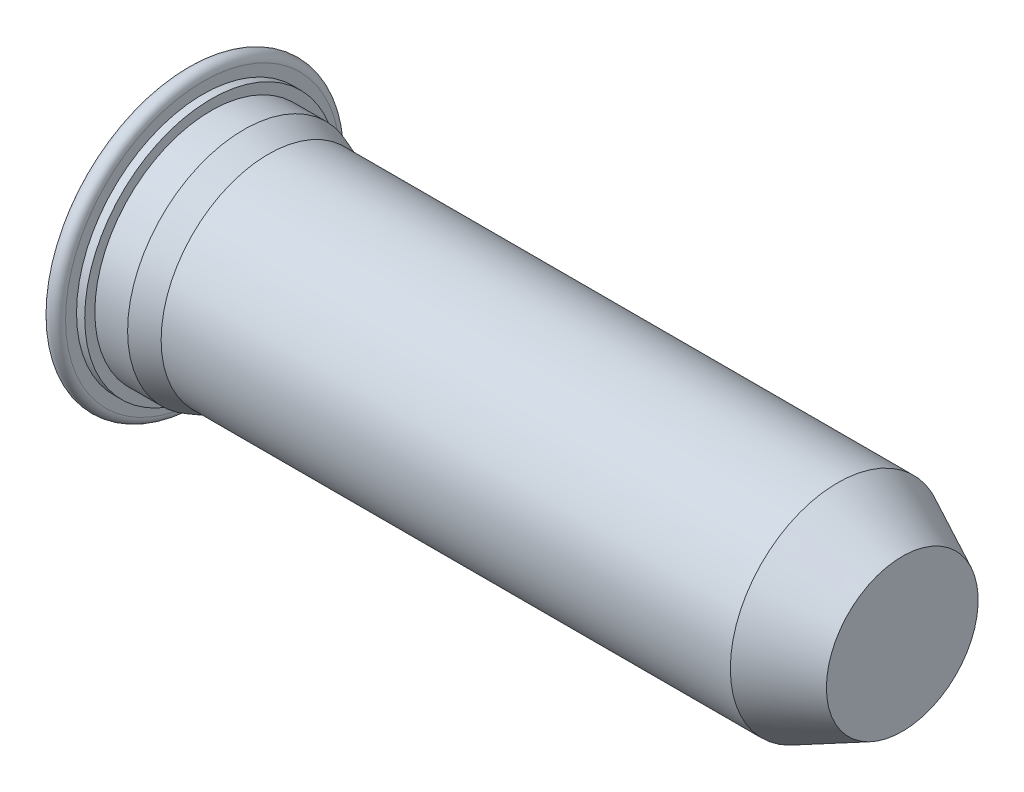
SolidWorks part; units mm, degrees
ref_plane "Plane1" through (0, 0, 0) normal (0, 0, 1) x (1, 0, 0)
ref_plane "Plane2" through (0, 0, 0) normal (0, 1, 0) x (1, 0, 0)
ref_plane "Plane3" through (0, 0, 0) normal (1, 0, 0) x (0, 0, -1)
sketch "BodySke" plane through (0, 0, 0) normal (0, 0, 1) x (1, 0, 0)
  line L0 (0, 0) -> (0, 3.8335)
  line L1 (0.458, 3.8385) -> (0.458, 3.5325)
  line L2 (20, 2.12) -> (18.1957, 3)
  line L3 (2.29, 3) -> (18.1957, 3)
  line L4 (20, 2.12) -> (20, 0)
  line L5 (20, 0) -> (0, 0)
  line L6 (0, 0) -> (50.554, 0) construction
  line L7 (0.458, 3.5325) -> (0.687, 3.5325)
  line L8 (1.6031, 3.25) -> (0.687, 3.25)
  line L9 (-9.525, 4.065) -> (9.525, 4.065) construction
  line L10 (0.687, 3.5325) -> (0.687, 3.25)
  line L11 (2.29, 3) -> (1.6031, 3.25)
  line L13 (9.525, -4.065) -> (-9.525, -4.065) construction
  line L14 (0.0051, 3.8385) -> (0.0051, 3.8335)
  line L15 (0, 3.8335) -> (0.0051, 3.8335)
  arc A0 (0.0051, 3.8385) -> (0.458, 3.8385) centre (0.2315, 3.8385) cw
  dimension "Length" = 20
  dimension "H_dia" = 8.13
  dimension "D1" = 0.0051
  dimension "D2" = 0.0051
  dimension "T_dim" = 0.458
  dimension "Diameter" = 6
  dimension "Neck_dia" = 6.5
  dimension "Neck_len" = 2.29
  dimension "D3" = 20
  dimension "D4" = 64
  dimension "D_dia" = 4.24
  dimension "Clinch_dia" = 7.065
  dimension "Clinch_ht" = 0.687
revolve "BaseBody" add sketch "BodySke" angle 360 about L6
cosmetic thread "ThreadCosmetic" [suppressed] parameters "Thread_length"=15.621, "Thread_minor"=4.8387
equation "' \"Diameter@BodySke\" = 6"
equation "' \"Length@BodySke\" = 20"
equation "' \"Neck_dia@BodySke\" = 6.5"
equation "' \"H_dia@BodySke\" = 8.13"
equation "' \"Neck_len@BodySke\" = 2.29"
equation "' \"D_dia@BodySke\" = 4.24"
equation "\"T_dim@BodySke\" = \"Neck_len@BodySke\" * 0.2"
equation "\"Clinch_dia@BodySke\" = ( \"H_dia@BodySke\" + \"Diameter@BodySke\" ) / 2"
equation "\"Clinch_ht@BodySke\" = \"T_dim@BodySke\" * 1.5"
